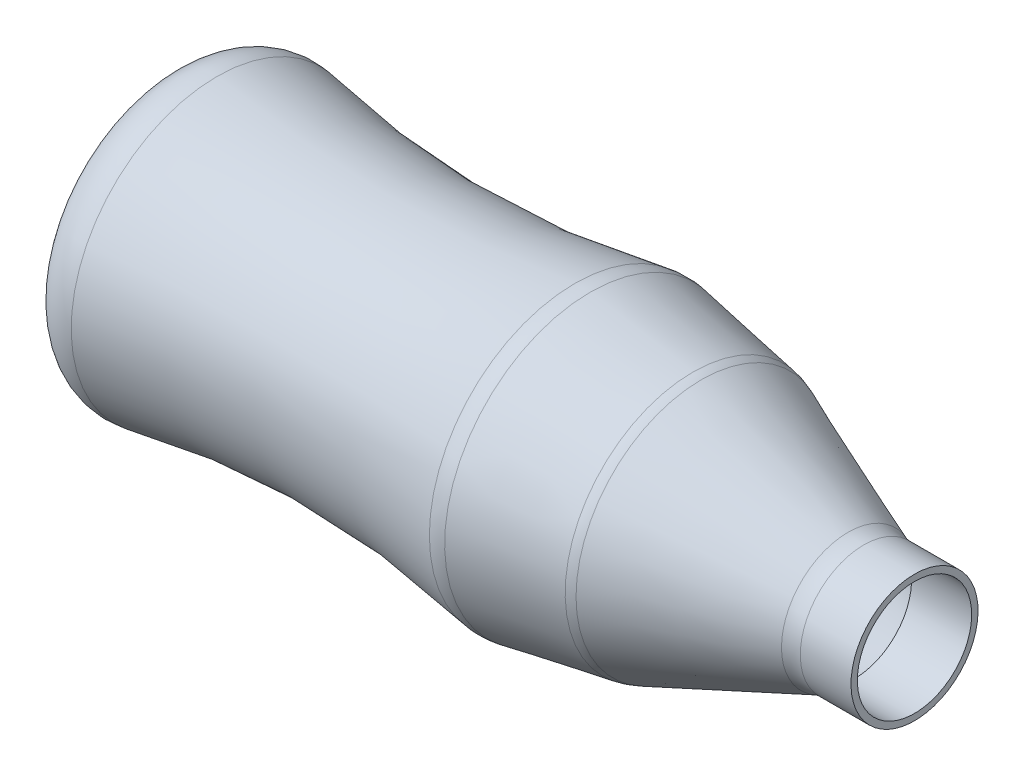
SolidWorks part; units mm, degrees
ref_plane "Front Plane" through (0, 0, 0) normal (0, 0, 1) x (1, 0, 0)
ref_plane "Top Plane" through (0, 0, 0) normal (0, 1, 0) x (1, 0, 0)
ref_plane "Right Plane" through (0, 0, 0) normal (1, 0, 0) x (0, 0, -1)
sketch "Sketch1" plane through (0, 0, 0) normal (0, 0, 1) x (1, 0, 0)
  line L0 (1352.8341, 0) -> (176.4171, 0) construction
  line L1 (0, 0) -> (0, 50000) construction
  line L2 (0, 0) -> (0, 24.57)
  line L3 (1.5, 0) -> (1.5, 24.57)
  line L4 (98.0577, 33.2235) -> (124.7138, 28.5496)
  line L5 (98.0371, 34.75) -> (125.1271, 30)
  line L6 (125.1271, 30) -> (162.5171, 15)
  line L7 (162.5171, 15) -> (176.4171, 15)
  line L8 (176.4171, 15) -> (176.4171, 13.5)
  line L9 (10, 34.57) -> (-27.0785, 34.57)
  line L10 (124.7138, 28.5496) -> (162.2274, 13.5)
  line L11 (162.2274, 13.5) -> (174.9171, 13.5)
  line L13 (0, 0) -> (1.5, 0)
  line L15 (174.9171, 13.5) -> (176.4171, 13.5)
  line L16 (176.4171, 15) -> (176.4171, 0) construction
  line L17 (174.9171, 13.5) -> (174.9171, 0) construction
  line L18 (174.9171, 0) -> (-50000, 0) construction
  arc A0 (0, 24.57) -> (11.6971, 34.4249) centre (10, 24.57) cw
  arc A1 (11.6971, 34.4249) -> (98.0371, 34.75) centre (54.0549, 250.3087) ccw
  arc A2 (1.5, 24.57) -> (11.4261, 32.9495) centre (10, 24.57) cw
  arc A3 (11.4261, 32.9495) -> (98.0577, 33.2235) centre (54.0549, 250.3087) ccw
  point P15 (0, 36.4392)
  dimension "D1" = 10
  dimension "D10" = 220
  dimension "D13" = 0
  dimension "D2" = 34.57
  dimension "D3" = 86.34
  dimension "D4" = 27.09
  dimension "D5" = 37.39
  dimension "D6" = 13.9
  dimension "D7" = 30
  dimension "D8" = 15
  dimension "D9" = 90
  dimension "D11" = 34.75
  dimension "D12" = 176.4171
  dimension "D14" = 1.5
revolve "Revolve1" add sketch "Sketch1" angle 360 about L18
fillet "Fillet1" radius 10 3 edges at (162.5171, 15, 0) (125.1271, 30, 0) (98.0371, 34.75, 0)
